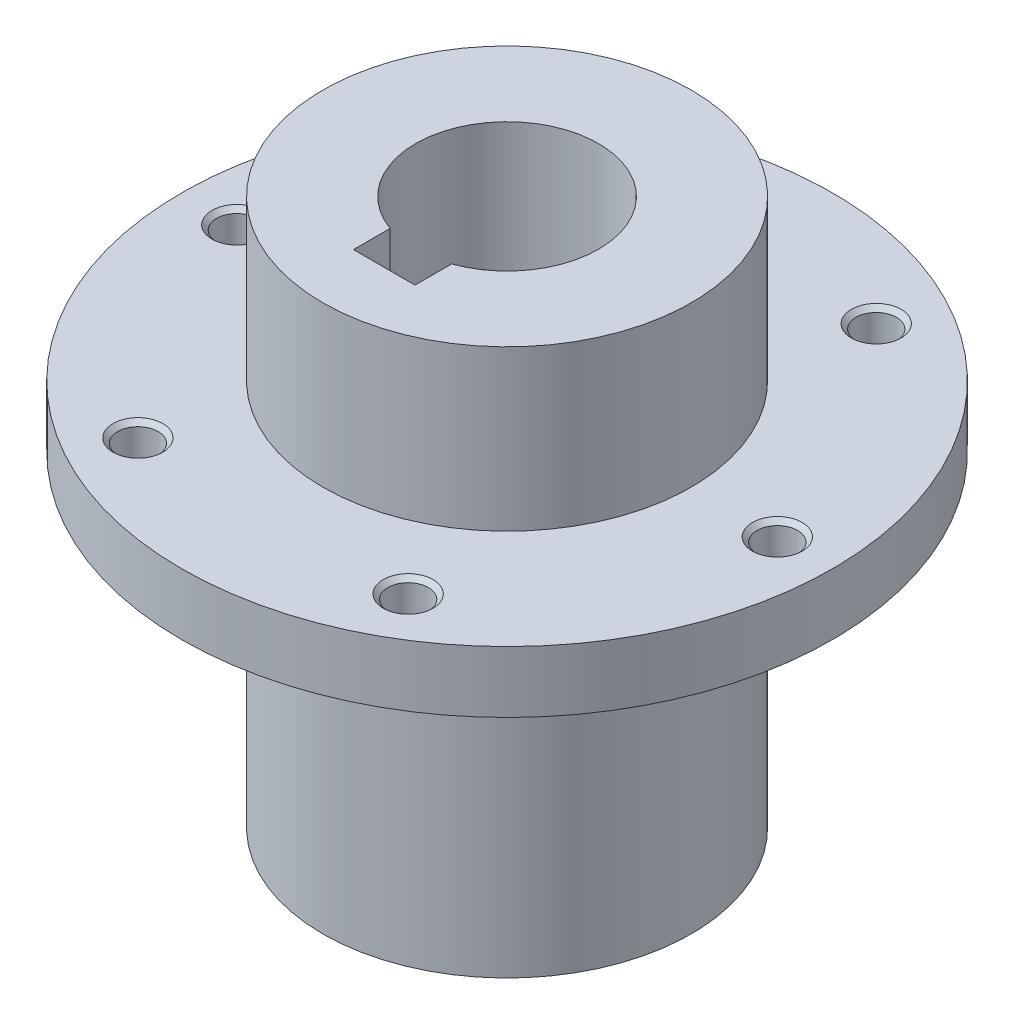
SolidWorks part; units mm, degrees
material "1060 合金"
ref_plane "前视基准面" through (0, 0, 0) normal (0, 0, 1) x (1, 0, 0)
ref_plane "上视基准面" through (0, 0, 0) normal (0, 1, 0) x (1, 0, 0)
ref_plane "右视基准面" through (0, 0, 0) normal (1, 0, 0) x (0, 0, -1)
sketch "草图1" plane through (0, 0, 0) normal (0, 1, 0) x (1, 0, 0)
  circle A0 centre (0, 0) radius 26.5
  dimension "D1" = 53
extrude "凸台-拉伸2" add sketch "草图1" along normal blind 5
sketch "草图3" plane through (0, 5, 0) normal (0, 1, 0) x (1, 0, 0)
  circle A0 centre (0, 0) radius 15
  dimension "D1" = 30
extrude "凸台-拉伸3" add sketch "草图3" along normal blind 13
sketch "草图4" plane through (0, 0, 0) normal (0, -1, 0) x (1, 0, 0)
  circle A0 centre (0, 0) radius 15
  dimension "D1" = 30
extrude "凸台-拉伸4" add sketch "草图4" along normal blind 26.5
hole_wizard "M4 螺纹孔1" positions "3D草图1" profile "草图6" tap size "M4" standard "GB"
sketch3d "3D草图1"
  line L2 (0, 0, 0) -> (27.585, 0, 0) construction
  line L4 (22, 0, 0) -> (22, 8.9561, 0) construction
  point P0 (22, 5, 0)
  dimension "D1" = 22
sketch "草图6" plane through (22, 5, 0) normal (1, 0, 0) x (0, 0, 1)
  line L0 (0, 0) -> (0, 5.9904)
  line L1 (0, 5.9904) -> (1.65, 4.999)
  line L2 (1.65, 4.999) -> (1.65, 0.375)
  line L3 (1.65, 0.375) -> (2.025, 0)
  line L5 (2.025, 0) -> (0, 0)
  line L6 (-1.65, 0.375) -> (-2.025, 0) construction
  line L10 (0, 5.9904) -> (-1.65, 4.999) construction
  line L11 (0, -6.35) -> (0, 107.95) construction
  dimension "螺纹孔钻头直径" = 3.3
  dimension "螺纹孔钻头深度" = 4.999
  dimension "近端锥形沉头孔直径" = 4.05
  dimension "近端锥形沉头孔角度" = 90
  dimension "导头角度" = 118
cosmetic thread "孔螺蚊线1" parameters "D1"=8, "D2"=4
pattern_circular "阵列(圆周)1" count 6 over 360 about axis through (0, 0, 0) along (0, 1, 0) of "M4 螺纹孔1"
cosmetic thread "孔螺蚊线2" parameters "D1"=8, "D2"=4
cosmetic thread "孔螺蚊线3" parameters "D1"=8, "D2"=4
cosmetic thread "孔螺蚊线4" parameters "D1"=8, "D2"=4
cosmetic thread "孔螺蚊线5" parameters "D1"=8, "D2"=4
cosmetic thread "孔螺蚊线6" parameters "D1"=8, "D2"=4
sketch "草图7" plane through (0, 18, 0) normal (0, 1, 0) x (1, 0, 0)
  circle A0 centre (0, 0) radius 7.45
  dimension "D1" = 14.9
extrude "切除-拉伸1" cut sketch "草图7" against normal up to surface (44.5 mm away) up to face at (0, -26.5, -15)
sketch "草图8" plane through (0, 18, 0) normal (0, 1, 0) x (1, 0, 0)
  line L0 (0, 0) -> (0, -13.5441) construction
  line L1 (-2.505, -10) -> (2.505, -10)
  line L2 (-2.505, -10) -> (-2.505, -5)
  line L3 (-2.505, -5) -> (2.505, -5)
  line L4 (2.505, -10) -> (2.505, -5)
  circle A0 centre (0, 0) radius 7.45 construction
  point P7 (0, -5)
  dimension "D1" = 5.01
  dimension "D2" = 10
  dimension "D3" = 5
extrude "切除-拉伸2" cut sketch "草图8" against normal up to surface (44.5 mm away) up to face at (0, -26.5, -7.45)
